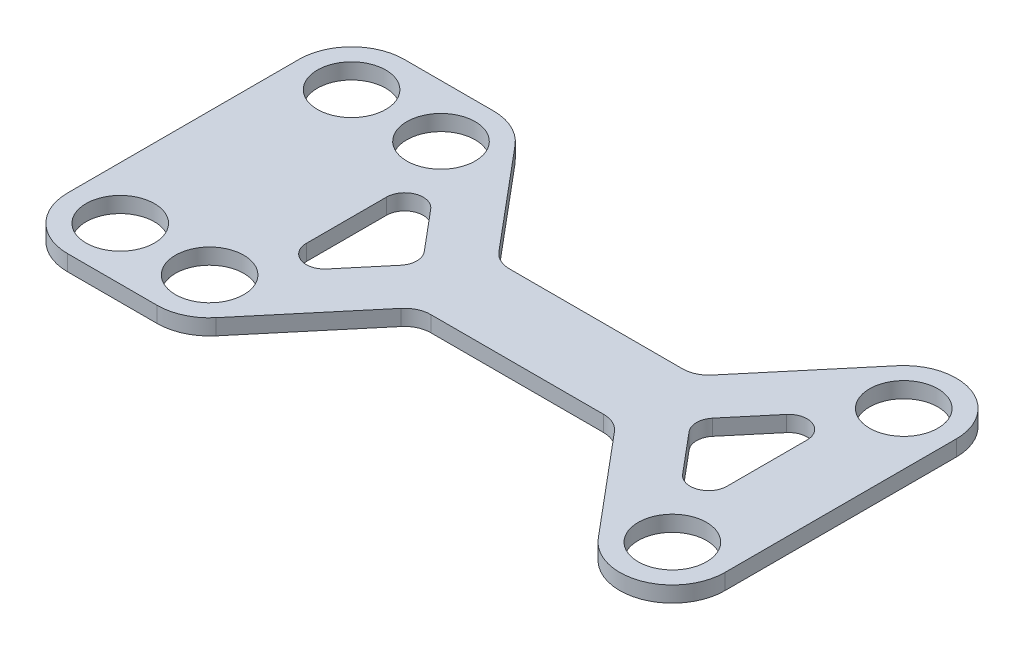
SolidWorks part; units mm, degrees
ref_plane "Front Plane" through (0, 0, 0) normal (0, 0, 1) x (1, 0, 0)
ref_plane "Top Plane" through (0, 0, 0) normal (0, 1, 0) x (1, 0, 0)
ref_plane "Right Plane" through (0, 0, 0) normal (1, 0, 0) x (0, 0, -1)
sketch "Sketch1" plane through (0, 0, 0) normal (0, 1, 0) x (1, 0, 0)
  line L0 (-15.8063, 0) -> (129.3245, 0) construction
  line L1 (0, 50.1132) -> (0, -46.1616) construction
  line L2 (17, 50.1132) -> (17, -46.1616) construction
  line L3 (105, 50.1132) -> (105, -46.1616) construction
  line L4 (129.3245, 22) -> (-15.8063, 22) construction
  line L5 (-10, -22) -> (-10, 22)
  line L6 (0, -32) -> (17, -32)
  line L7 (0, 32) -> (17, 32)
  line L8 (115, 22) -> (115, -22)
  line L9 (24.6604, 28.4279) -> (40.7223, 9.2861)
  line L10 (97.3396, 28.4279) -> (81.2777, 9.2861)
  line L11 (77.4474, 7.5) -> (44.5526, 7.5)
  line L12 (97.3396, -28.4279) -> (81.2777, -9.2861)
  line L13 (77.4474, -7.5) -> (44.5526, -7.5)
  line L14 (24.6604, -28.4279) -> (40.7223, -9.2861)
  arc A0 (0, 32) -> (-10, 22) centre (0, 22) ccw
  arc A1 (115, -22) -> (97.3396, -28.4279) centre (105, -22) cw
  arc A2 (115, 22) -> (97.3396, 28.4279) centre (105, 22) ccw
  arc A3 (24.6604, -28.4279) -> (17, -32) centre (17, -22) cw
  arc A4 (44.5526, 7.5) -> (40.7223, 9.2861) centre (44.5526, 12.5) cw
  arc A5 (0, -32) -> (-10, -22) centre (0, -22) cw
  arc A6 (81.2777, 9.2861) -> (77.4474, 7.5) centre (77.4474, 12.5) cw
  arc A7 (77.4474, -7.5) -> (81.2777, -9.2861) centre (77.4474, -12.5) cw
  arc A8 (40.7223, -9.2861) -> (44.5526, -7.5) centre (44.5526, -12.5) cw
  arc A12 (24.6604, 28.4279) -> (17, 32) centre (17, 22) ccw
  point P35 (42.221, 7.5)
  point P38 (79.779, 7.5)
  point P41 (79.779, -7.5)
  point P44 (42.221, -7.5)
  dimension "D4" = 10
  dimension "D5" = 7.5
  dimension "D6" = 40
  dimension "D7" = 40
  dimension "D8" = 5
  dimension "D10" = 10
  dimension "D1" = 22
  dimension "D2" = 88
  dimension "D3" = 105
extrude "base" add sketch "Sketch1" against normal blind 3
sketch "Sketch2" plane through (0, 0, 0) normal (0, 1, 0) x (1, 0, 0)
  circle A0 centre (0, 22) radius 6.5
  circle A1 centre (17, 22) radius 6.5
  circle A2 centre (105, 22) radius 6.5
  circle A3 centre (105, -22) radius 6.5
  circle A4 centre (17, -22) radius 6.5
  circle A5 centre (0, -22) radius 6.5
  arc A6 (0, 32) -> (-10, 22) centre (0, 22) ccw construction
  arc A7 (24.6604, 28.4279) -> (17, 32) centre (17, 22) ccw construction
  arc A8 (-10, -22) -> (0, -32) centre (0, -22) ccw construction
  arc A11 (115, 22) -> (97.3396, 28.4279) centre (105, 22) ccw construction
  arc A12 (17, -32) -> (24.6604, -28.4279) centre (17, -22) ccw construction
  arc A13 (97.3396, -28.4279) -> (115, -22) centre (105, -22) ccw construction
  dimension "D1" = 13
extrude "holes" cut sketch "Sketch2" against normal through all
sketch "Sketch3" plane through (0, 0, 0) normal (0, 1, 0) x (-1, 0, 0)
  line L0 (-21, -7.6168) -> (-21, 7.6168)
  line L2 (-33.0619, -2.8582) -> (-17, -22)
  line L3 (-33.5724, -2.2498) -> (-27.1812, -9.8666)
  line L5 (-17, 22) -> (-33.0619, 2.8582)
  line L6 (-27.1812, 9.8666) -> (-33.5724, 2.2498)
  line L7 (-105, -22) -> (-88.9381, -2.8582)
  line L8 (-94.8188, -9.8666) -> (-88.4276, -2.2498)
  line L9 (-101, -7.6168) -> (-101, 7.6168)
  line L10 (-88.9381, 2.8582) -> (-105, 22)
  line L11 (-88.4276, 2.2498) -> (-94.8188, 9.8666)
  arc A0 (-27.1812, -9.8666) -> (-21, -7.6168) centre (-24.5, -7.6168) ccw
  arc A1 (-33.5724, 2.2498) -> (-33.5724, -2.2498) centre (-30.8913, 0) ccw
  arc A2 (-21, 7.6168) -> (-27.1812, 9.8666) centre (-24.5, 7.6168) ccw
  arc A3 (-88.4276, -2.2498) -> (-88.4276, 2.2498) centre (-91.1087, 0) ccw
  arc A4 (-101, -7.6168) -> (-94.8188, -9.8666) centre (-97.5, -7.6168) ccw
  arc A5 (-94.8188, 9.8666) -> (-101, 7.6168) centre (-97.5, 7.6168) ccw
  point P10 (-17, -22)
  point P28 (-105, -22)
  dimension "D2" = 10
  dimension "D3" = 3.5
  dimension "D4" = 4
  dimension "D1" = 10
  dimension "D5" = 10
  dimension "D6" = 10
  dimension "D7" = 3.5
  dimension "D8" = 4
extrude "cutaway" cut sketch "Sketch3" against normal through all
